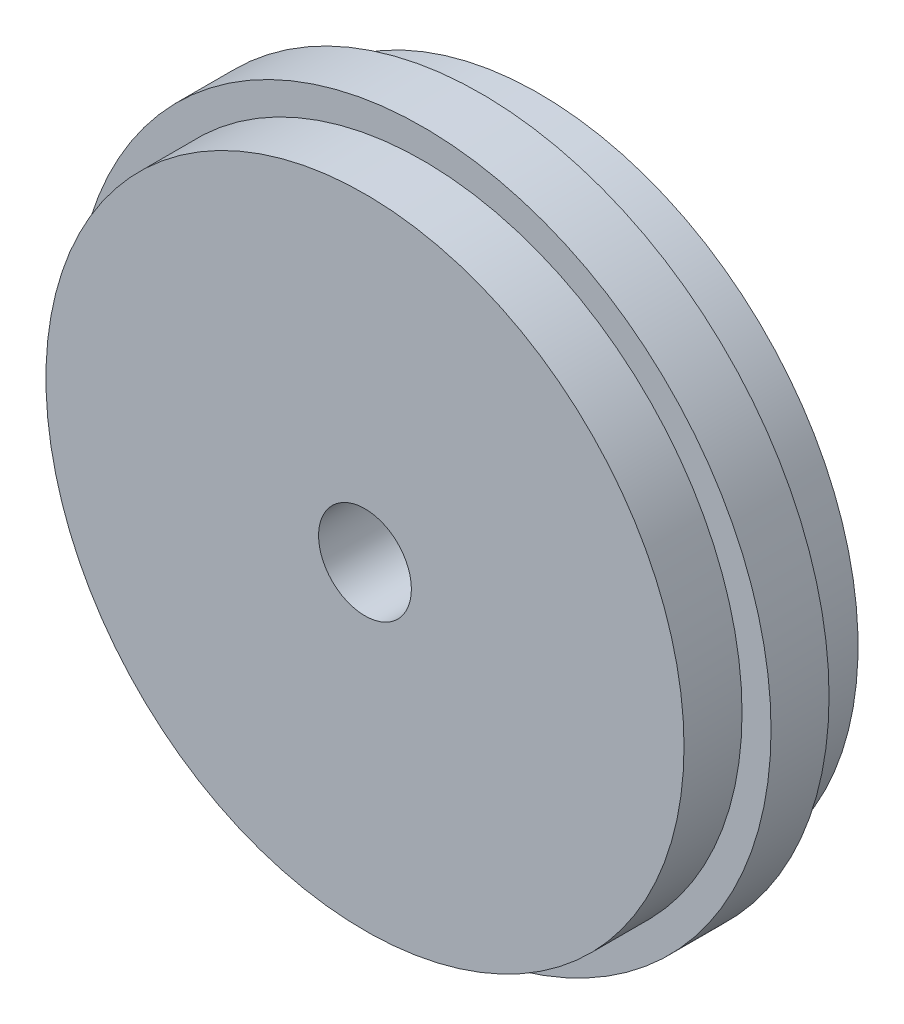
SolidWorks part; units mm, degrees
ref_plane "Front Plane" through (0, 0, 0) normal (0, 0, 1) x (1, 0, 0)
ref_plane "Top Plane" through (0, 0, 0) normal (0, 1, 0) x (1, 0, 0)
ref_plane "Right Plane" through (0, 0, 0) normal (1, 0, 0) x (0, 0, -1)
sketch "Sketch1" plane through (0, 0, 0) normal (0, 0, 1) x (1, 0, 0)
  circle A0 centre (0, 0) radius 60
  dimension "D1" = 120
extrude "Boss-Extrude1" add sketch "Sketch1" along normal blind 10
sketch "Sketch2" plane through (0, 0, 10) normal (0, 0, 1) x (1, 0, 0)
  circle A0 centre (0, 0) radius 55
  dimension "D1" = 110
extrude "Boss-Extrude2" add sketch "Sketch2" along normal blind 10
sketch "Sketch5" plane through (0, 0, 0) normal (0, 0, -1) x (-1, 0, 0)
  circle A0 centre (0, 0) radius 55
  dimension "D1" = 110
extrude "Boss-Extrude4" add sketch "Sketch5" along normal blind 10
sketch "Sketch3" plane through (0, 0, 20) normal (0, 0, 1) x (1, 0, 0)
  circle A0 centre (0, 0) radius 8
  dimension "D1" = 16
extrude "Cut-Extrude2" cut sketch "Sketch3" against normal through all
